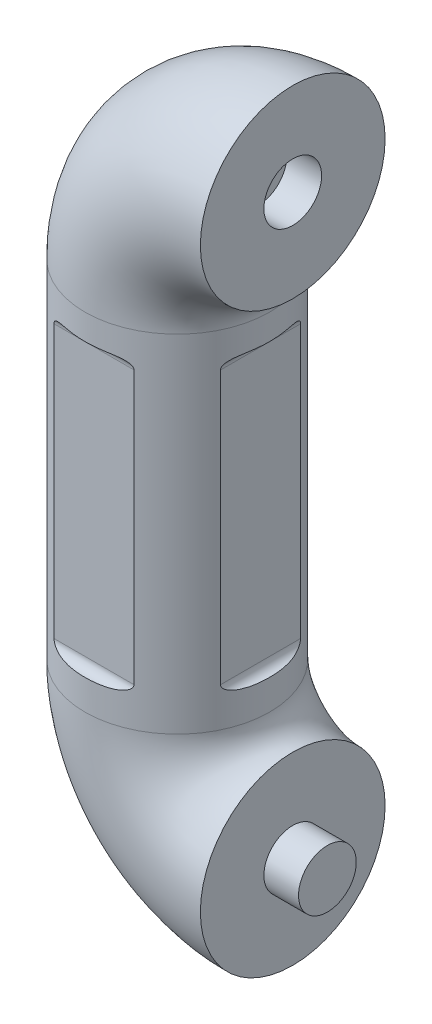
SolidWorks part; units mm, degrees
material "ABS"
ref_plane "Front Plane" through (0, 0, 0) normal (0, 0, 1) x (1, 0, 0)
ref_plane "Top Plane" through (0, 0, 0) normal (0, 1, 0) x (1, 0, 0)
ref_plane "Right Plane" through (0, 0, 0) normal (1, 0, 0) x (0, 0, -1)
sketch "Sketch1" plane through (0, 0, 0) normal (0, 0, 1) x (1, 0, 0)
  line L0 (0, 0) -> (-10, 0)
  line L1 (-110, 100) -> (-110, 400)
  line L2 (-10, 500) -> (0, 500)
  arc A0 (-110, 400) -> (-10, 500) centre (-10, 400) cw
  arc A1 (-110, 100) -> (-10, 0) centre (-10, 100) ccw
  dimension "D1" = 100
sweep "Sweep1" add path "Sketch1" circular profile diameter 160 parameters "D3"=160
sketch "Sketch6" plane through (-10, 0, 0) normal (1, 0, 0) x (0, 0, -1)
  circle A0 centre (0, 500) radius 25
extrude "Cut-Extrude1" cut sketch "Sketch6" against normal blind 30
sketch "Sketch7" plane through (-10, 0, 0) normal (1, 0, 0) x (0, 0, -1)
  circle A0 centre (0, 0) radius 25
extrude "Boss-Extrude1" add sketch "Sketch7" along normal blind 30
sketch "Sketch8" plane through (-10, 0, 0) normal (1, 0, 0) x (0, 0, -1)
  circle A0 centre (0, 0) radius 25
  circle A1 centre (0, 0) radius 35
  circle A2 centre (0, 0) radius 45
  circle A3 centre (0, 0) radius 50
  circle M1 centre (0, 0) radius 25
extrude "Cut-Extrude2" cut sketch "Sketch8" against normal through all from offset 100 contours A3 A2 | A1 M1 offset against normal yes
sketch "Sketch9" plane through (0, 0, 0) normal (0, 0, 1) x (1, 0, 0)
  line L0 (-190, 400) -> (-190, 370)
  line L1 (-190, 400) -> (-190, 100) construction
  line L2 (-190, 370) -> (-190, 133.9437) construction
  line L3 (-182.1098, 370) -> (-182.1098, 133.9437)
  line L4 (-197.8902, 370) -> (-197.8902, 133.9437)
  arc A0 (-182.1098, 370) -> (-197.8902, 370) centre (-190, 370) ccw
  arc A1 (-197.8902, 133.9437) -> (-182.1098, 133.9437) centre (-190, 133.9437) ccw
  point P5 (-190, 251.9718)
  dimension "D1" = 30
extrude "Cut-Extrude3" cut sketch "Sketch9" along normal through all both and the other way through all
pattern_circular "CirPattern1" count 4 over 360 about axis through (-110, 0, 0) along (0, 1, 0) of "Cut-Extrude3"
